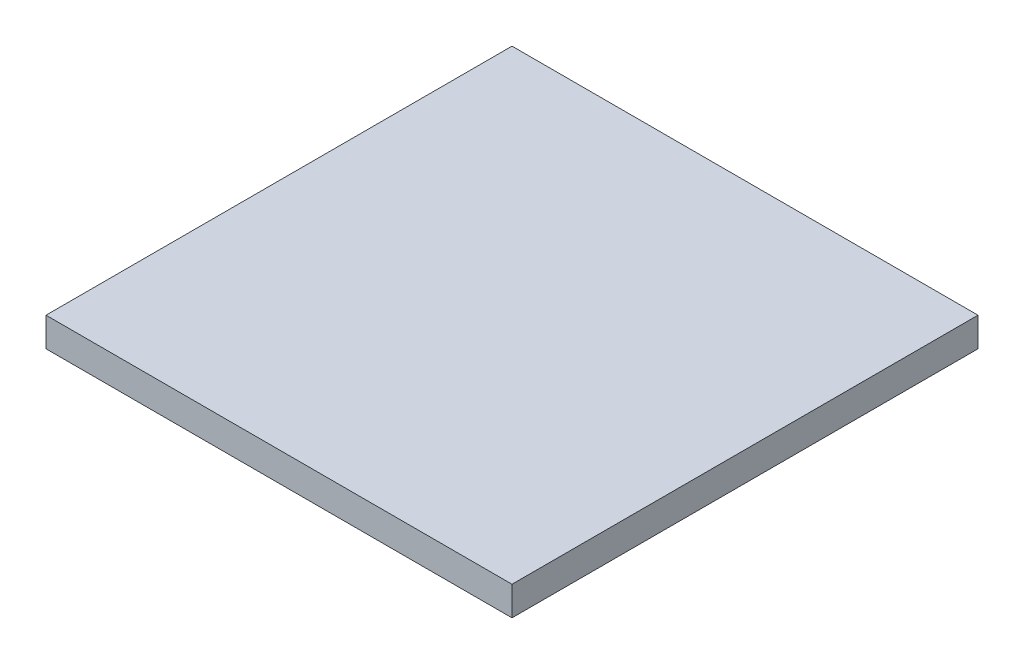
SolidWorks part; units mm, degrees
ref_plane "Front Plane" through (0, 0, 0) normal (0, 0, 1) x (1, 0, 0)
ref_plane "Top Plane" through (0, 0, 0) normal (0, 1, 0) x (1, 0, 0)
ref_plane "Right Plane" through (0, 0, 0) normal (1, 0, 0) x (0, 0, -1)
sketch "Sketch1" plane through (0, 0, 0) normal (0, 1, 0) x (1, 0, 0)
  line L1 (-101.6, -101.6) -> (101.6, -101.6)
  line L2 (-101.6, -101.6) -> (-101.6, 101.6)
  line L3 (-101.6, 101.6) -> (101.6, 101.6)
  line L4 (101.6, -101.6) -> (101.6, 101.6)
  line L5 (-101.6, -101.6) -> (101.6, 101.6) construction
  line L6 (-101.6, 101.6) -> (101.6, -101.6) construction
  point P0 (0, 0)
  dimension "D1" = 203.2
  dimension "D2" = 203.2
extrude "Boss-Extrude1" add sketch "Sketch1" along normal blind 12.7
